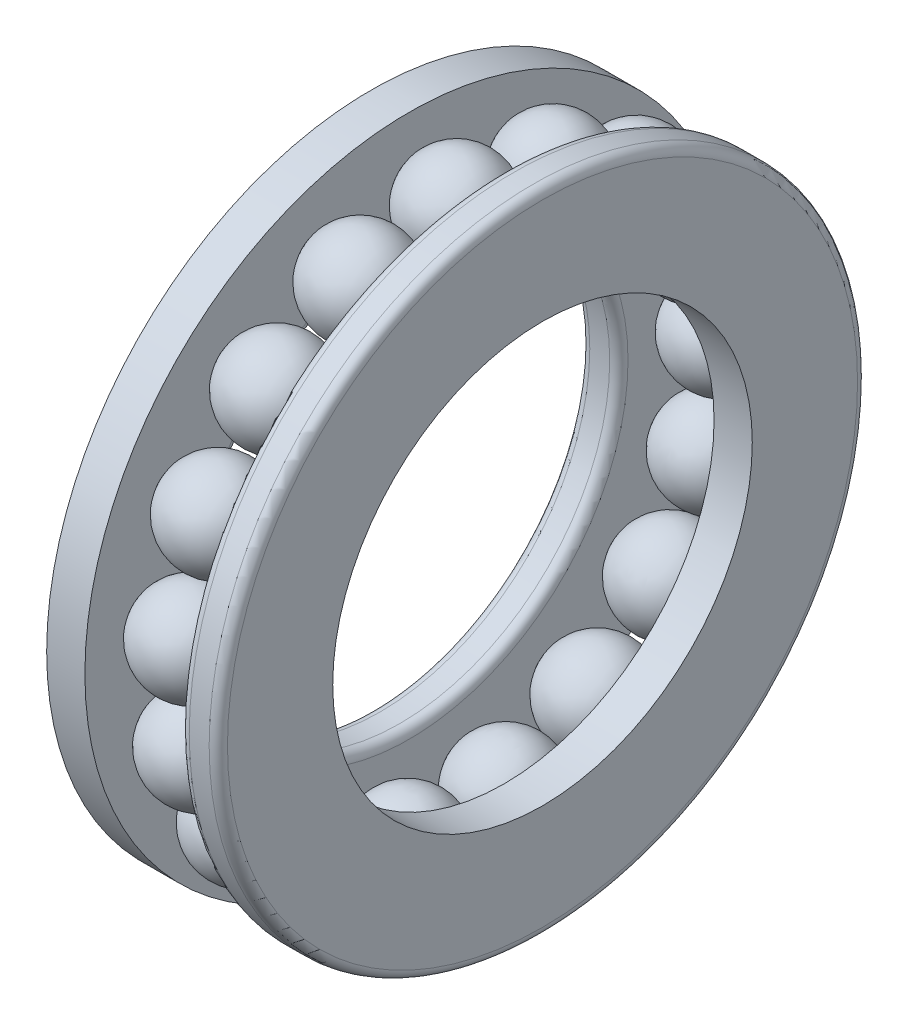
SolidWorks part; units mm, degrees
ref_plane "Plane1" through (0, 0, 0) normal (0, 0, 1) x (1, 0, 0)
ref_plane "Plane2" through (0, 0, 0) normal (0, 1, 0) x (1, 0, 0)
ref_plane "Plane3" through (0, 0, 0) normal (1, 0, 0) x (0, 0, -1)
sketch "Clipboard" plane through (0, 0, 0) normal (0, 0, 1) x (1, 0, 0)
  line L0 (-10, 0) -> (10, 0) construction
  line L1 (0, 0) -> (21.3836, -6.5376)
  line L2 (0, 0) -> (27.3662, 35.0271)
  line L3 (0, 0) -> (13.7666, -17.6205)
  line L4 (0, 0) -> (-22.3471, -0.7804)
  dimension "BallCLRad" = 44.45
  dimension "Count" = 52
  dimension "Show_count" = 52
  dimension "Max_count" = 17
  dimension "Min_count" = 2
sketch "InnRacSke" plane through (0, 0, 0) normal (0, 0, 1) x (1, 0, 0)
  line L1 (-7.9248, 34.925) -> (-14.2875, 34.925)
  line L2 (-14.2875, 34.925) -> (-14.2875, 53.975)
  line L3 (-14.2875, 53.975) -> (-7.9248, 53.975)
  line L4 (-7.9248, 53.975) -> (-7.9248, 34.925)
  line L5 (-34.925, 0) -> (34.925, 0) construction
  line L6 (0, 0) -> (0, 25.4) construction
  dimension "ID" = 69.85
  dimension "OD" = 107.95
  dimension "Width" = 28.575
  dimension "gap" = 15.8496
revolve "Race" add sketch "InnRacSke" angle 360 about L5
ref_axis "Axis1" through (-50, 0, 0) along (1, 0, 0)
sketch "BalDetSke" plane through (0, 0, 0) normal (0, 0, 1) x (1, 0, 0)
  line L0 (-7.9375, 44.45) -> (7.9375, 44.45)
  line L1 (-14.5732, 44.45) -> (14.5732, 44.45) construction
  arc A0 (7.9375, 44.45) -> (-7.9375, 44.45) centre (0, 44.45) cw
  dimension "BallCLRad" = 44.45
  dimension "Ball_diameter" = 15.875
revolve "BallDetailed" add sketch "BalDetSke" angle 360 about L1
sketch "BalSimSke" plane through (0, 0, 0) normal (0, 0, 1) x (1, 0, 0)
  line L0 (-25.4, 0) -> (25.4, 0) construction
  circle A0 centre (0, 44.45) radius 7.9375
  dimension "BallCLRad" = 44.45
  dimension "Ball_diameter" = 15.875
revolve "BallsSimplified" [suppressed] add sketch "BalSimSke" angle 360 about L0
mirror "Mirror1" about plane through (0, 0, 0) normal (1, 0, 0) of "Race"
fillet "Fillet" radius 1.524 4 edges at (7.9248, 0, -53.975) (14.2875, 0, -53.975) (-7.9248, 0, -34.925) (-14.2875, 0, -34.925)
pattern_circular "BallsDetailed" count 17 every 21.176 about axis through (-50, 0, 0) along (1, 0, 0) of "BallDetailed"
sketch "CagSpiSke" plane through (0, 0, 0) normal (0, 0, 1) x (1, 0, 0)
  line L0 (1.9844, 35.7188) -> (1.9844, 53.1812)
  line L1 (1.9844, 53.1812) -> (-1.2169, 53.1812)
  line L2 (-1.2169, 53.1812) -> (-1.2169, 35.7188)
  line L3 (-1.2169, 35.7188) -> (1.9844, 35.7188)
  line L4 (-34.925, 0) -> (34.925, 0) construction
  line L5 (0, 0) -> (0, 50.8) construction
  dimension "Thickness" = 3.9688
  dimension "ID" = 71.4375
  dimension "OD" = 106.3625
revolve "CageSpine" [suppressed] add sketch "CagSpiSke" angle 360 about L4
equation "\"BallCLRad@Clipboard\" =  ( \"OD@InnRacSke\" + \"ID@InnRacSke\" )  / 4"
equation "\"BallCLRad@BalSimSke\" = \"BallCLRad@Clipboard\""
equation "\"BallCLRad@BalDetSke\" = \"BallCLRad@Clipboard\""
equation "\"gap@InnRacSke\" = \"Ball_diameter@BalDetSke\" - 0.001"
equation "\"Ball_diameter@BalSimSke\" = \"Ball_diameter@BalDetSke\""
equation "\"Max_count@Clipboard\" = int( 3.14159265 / atn(( \"Ball_diameter@BalDetSke\" / 2) / sqr( \"BallCLRad@Clipboard\"  *  \"BallCLRad@Clipboard\" - ( \"Ball_diameter@BalDetSke\" / 2) *  ( \"Ball_diameter@BalDetSke\" / 2))))"
equation "\"Max_count@Clipboard\" = ((sgn( \"Max_count@Clipboard\" - \"Count@Clipboard\" )-1)*( \"Max_count@Clipboard\" - \"Count@Clipboard\" ))/-2+ \"Count@Clipboard\""
equation "\"Count@BallsDetailed\" = int( \"Show_count@Clipboard\" ) "
equation "\"Count@BallsDetailed\" = ((sgn( \"Count@BallsDetailed\" - \"Max_count@Clipboard\" )-1)*( \"Count@BallsDetailed\" - \"Max_count@Clipboard\" ))/-2+ \"Max_count@Clipboard\""
equation "\"Count@BallsDetailed\" = ((sgn( \"Count@BallsDetailed\" - \"Min_count@Clipboard\" )+1)*( \"Count@BallsDetailed\" - \"Min_count@Clipboard\"))/2 +\"Min_count@Clipboard\""
equation "\"Angle@BallsDetailed\" = 360.0 / \"Max_count@Clipboard\""
equation "\"Angle@CageSpine\" =  \"Angle@BallsDetailed\" * ( \"Count@BallsDetailed\" -1 + int( \"Count@BallsDetailed\" / \"Max_count@Clipboard\" ) )  + 0.001 -  int( \"Count@BallsDetailed\" / \"Max_count@Clipboard\" ) * 0.001"
equation "\"Angle@CageSpine\" =  \"Angle@CageSpine\" * int( \"Min_count@Clipboard\" / 2) + int(1 / \"Min_count@Clipboard\")  * 0.001"
equation "\"Thickness@CagSpiSke\" =  \"Ball_diameter@BalDetSke\" * 0.25"
equation "\"OD@CagSpiSke\" = ( \"OD@InnRacSke\" + ( \"BallCLRad@Clipboard\" * 2 + \"Ball_diameter@BalDetSke\" )) / 2"
equation "\"ID@CagSpiSke\" = ( \"ID@InnRacSke\" + ( \"BallCLRad@Clipboard\" * 2 - \"Ball_diameter@BalDetSke\" )) / 2"
